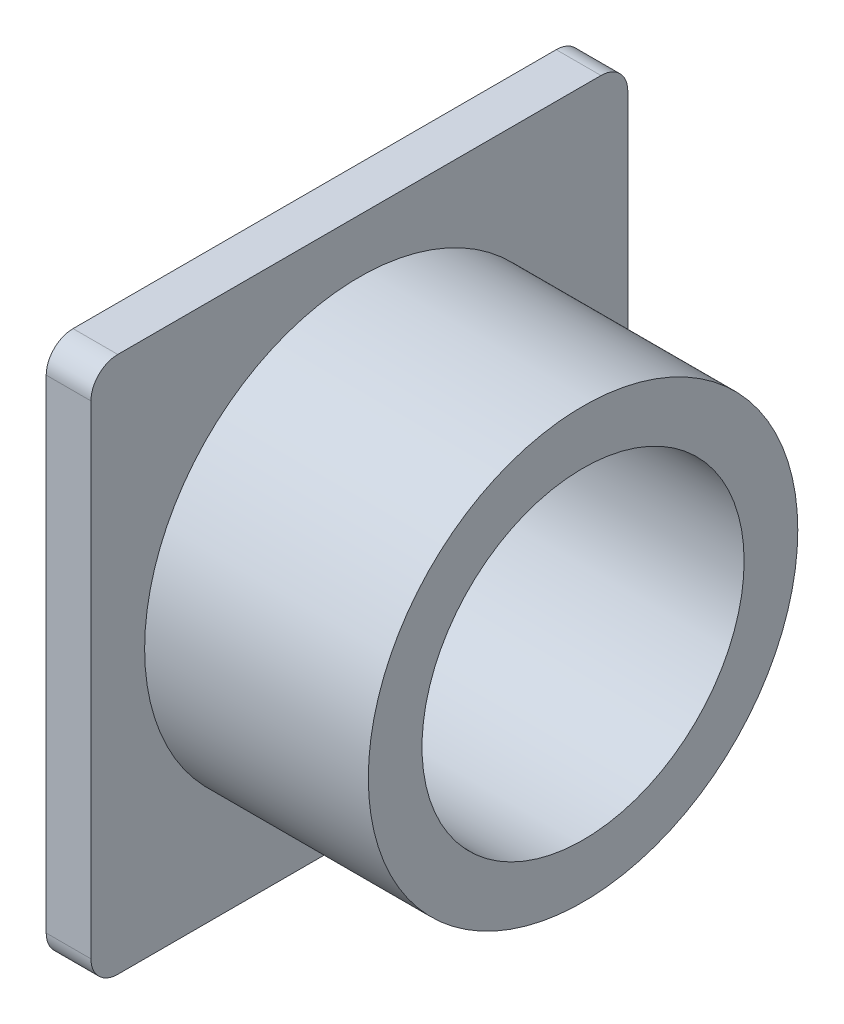
SolidWorks part; units mm, degrees
ref_plane "Płaszczyzna przednia" through (0, 0, 0) normal (0, 0, 1) x (1, 0, 0)
ref_plane "Płaszczyzna górna" through (0, 0, 0) normal (0, 1, 0) x (1, 0, 0)
ref_plane "Płaszczyzna prawa" through (0, 0, 0) normal (1, 0, 0) x (0, 0, -1)
sketch "Szkic2" plane through (0, 0, 0) normal (1, 0, 0) x (0, 0, -1)
  line L1 (3, 0) -> (57, 0)
  line L2 (0, 3) -> (0, 57)
  line L3 (3, 60) -> (57, 60)
  line L4 (60, 3) -> (60, 57)
  line L5 (3, 0) -> (42.6554, 0)
  line L6 (0, 3) -> (0, 31.4913)
  arc A0 (57, 60) -> (60, 57) centre (57, 57) cw
  arc A2 (57, 0) -> (60, 3) centre (57, 3) ccw
  arc A5 (3, 0) -> (0, 3) centre (3, 3) cw
  arc A7 (0, 57) -> (3, 60) centre (3, 57) cw
  dimension "D1" = 3
extrude "Dodanie-wyciągnięcie1" add sketch "Szkic2" along normal blind 5 contours A7 L2 A5 L1 A2 L4 A0 L3
sketch "Szkic3" plane through (5, 0, 0) normal (1, 0, 0) x (0, 0, -1)
  circle A0 centre (30, 30) radius 24
  dimension "D1" = 48
extrude "Dodanie-wyciągnięcie2" add sketch "Szkic3" along normal blind 25
hole_wizard "Otwór Ø36.0 (36)1" positions "Szkic5" profile "Szkic4" hole size "Ø36.0" standard "DIN" end condition through all
sketch "Szkic5" plane through (30, 0, 0) normal (1, 0, 0) x (0, 0, -1)
  point P0 (30, 30)
sketch "Szkic4" plane through (30, 30, -30) normal (0, 1, 0) x (0, 0, -1)
  line L0 (0, 0) -> (0, 30)
  line L1 (0, 30) -> (18, 30)
  line L2 (18, 30) -> (18, 0)
  line L5 (18, 0) -> (0, 0)
  line L11 (0, -6.35) -> (0, 107.95) construction
  dimension "Średnica otworu na wylot" = 36
  dimension "Głębokość otworu na wylot" = 30
